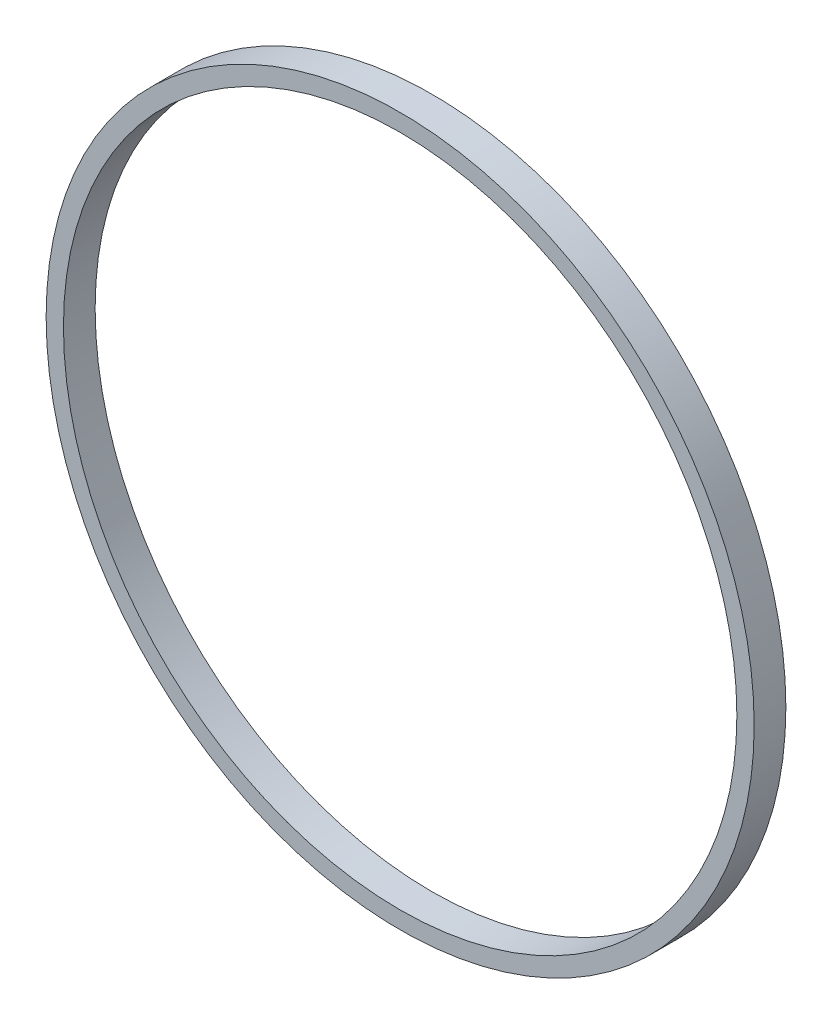
SolidWorks part; units mm, degrees
ref_plane "Front Plane" through (0, 0, 0) normal (0, 0, 1) x (1, 0, 0)
ref_plane "Top Plane" through (0, 0, 0) normal (0, 1, 0) x (1, 0, 0)
ref_plane "Right Plane" through (0, 0, 0) normal (1, 0, 0) x (0, 0, -1)
sketch "Sketch1" plane through (0, 0, 0) normal (0, 0, 1) x (1, 0, 0)
  circle A0 centre (0, 0) radius 46.6852
  circle A1 centre (0, 0) radius 49.0855
  dimension "D1" = 93.3704
  dimension "D2" = 98.171
extrude "Boss-Extrude1" add sketch "Sketch1" along normal blind 4.3942
